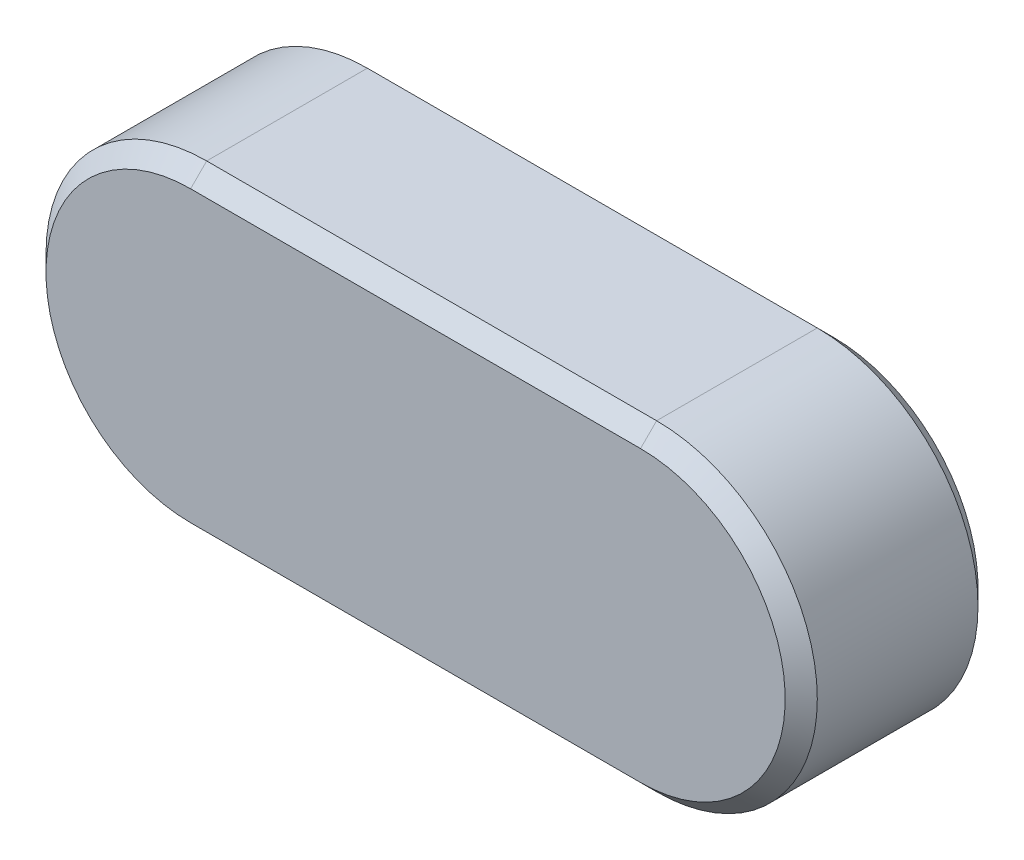
SolidWorks part; units mm, degrees
ref_plane "Front" through (0, 0, 0) normal (0, 0, 1) x (1, 0, 0)
ref_plane "Top" through (0, 0, 0) normal (0, 1, 0) x (1, 0, 0)
ref_plane "Right" through (0, 0, 0) normal (1, 0, 0) x (0, 0, -1)
sketch "Sketch1" plane through (0, 0, 0) normal (0, 0, 1) x (1, 0, 0)
  line L0 (0, 2.5) -> (-7, 2.5)
  line L1 (-7, -2.5) -> (0, -2.5)
  arc A0 (-7, 2.5) -> (-7, -2.5) centre (-7, 0) ccw
  arc A1 (0, -2.5) -> (0, 2.5) centre (0, 0) ccw
  dimension "b" = 5
  dimension "l" = 12
extrude "Extrude1" add sketch "Sketch1" along normal blind 3
sketch "Sketch2" plane through (0, 0, 0) normal (0, 0, 1) x (1, 0, 0)
  line L0 (0, 2.5) -> (-7, 2.5) construction
  line L1 (-9.5, 2.5) -> (2.5, 2.5)
  line L2 (-9.5, 2.5) -> (-9.5, -2.5)
  line L3 (-9.5, -2.5) -> (2.5, -2.5)
  line L4 (2.5, 2.5) -> (2.5, -2.5)
  line L5 (-7, -2.5) -> (0, -2.5) construction
  arc A0 (-7, 2.5) -> (-7, -2.5) centre (-7, 0) ccw construction
  arc A1 (0, -2.5) -> (0, 2.5) centre (0, 0) ccw construction
extrude "Extrude2" [suppressed] add sketch "Sketch2" along normal blind 3
sketch "Sketch3" plane through (0, 0, 0) normal (0, 0, 1) x (1, 0, 0)
  line L0 (-7, -2.5) -> (0, -2.5) construction
  line L1 (-7, -2.5) -> (2.5, -2.5)
  line L3 (-7, 2.5) -> (2.5, 2.5)
  line L4 (2.5, -2.5) -> (2.5, 2.5)
  arc A1 (-7, 2.5) -> (-7, -2.5) centre (-7, 0) ccw
  arc A2 (0, -2.5) -> (0, 2.5) centre (0, 0) ccw construction
  arc A3 (-7, 2.5) -> (-7, -2.5) centre (-7, 0) ccw construction
extrude "Extrude3" [suppressed] add sketch "Sketch3" along normal blind 3
chamfer "Chamfer1" distance 0.25 angle 45 8 edges at (-3.5, 2.5, 0) (-3.5, -2.5, 0) (-3.5, 2.5, 3) (-3.5, -2.5, 3) (-9.5, 0, 0) (-9.5, 0, 3) (2.5, 0, 0) (2.5, 0, 3)
equation "\"D1@Extrude2\" = \"h@Extrude1\""
equation "\"D1@Extrude3\" = \"h@Extrude1\""
